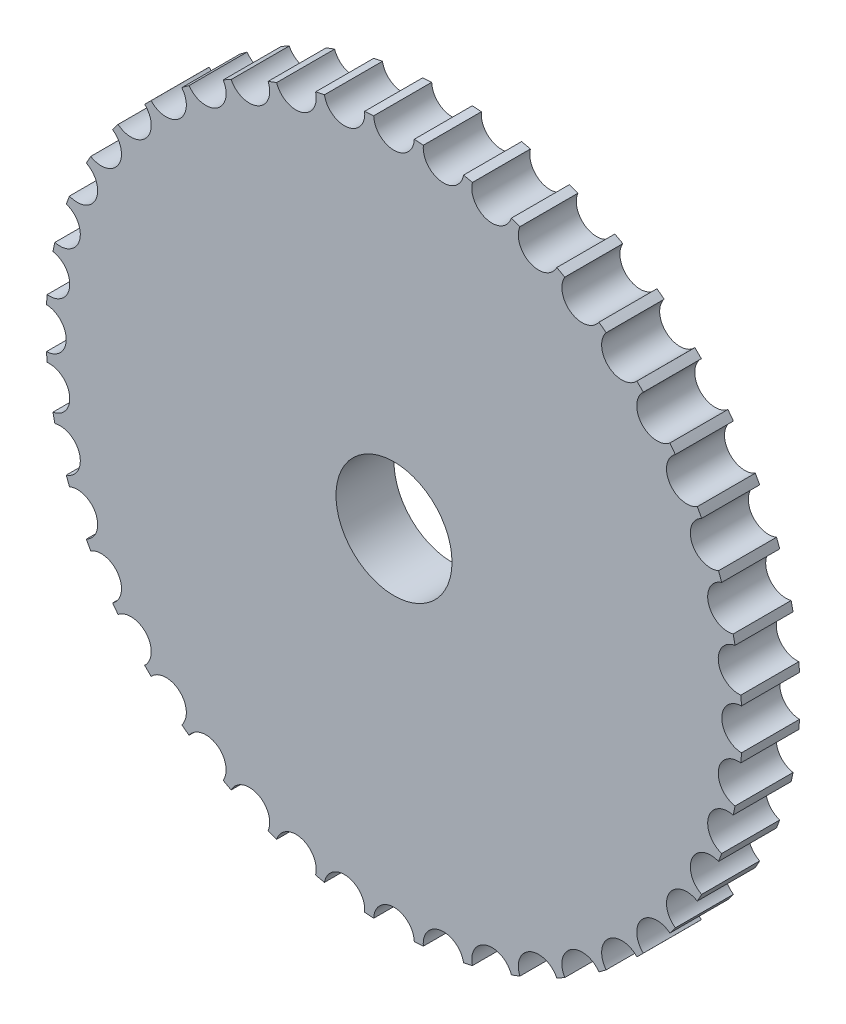
SolidWorks part; units mm, degrees
ref_plane "Front Plane" through (0, 0, 0) normal (0, 0, 1) x (1, 0, 0)
ref_plane "Top Plane" through (0, 0, 0) normal (0, 1, 0) x (1, 0, 0)
ref_plane "Right Plane" through (0, 0, 0) normal (1, 0, 0) x (0, 0, -1)
sketch "Sketch1" plane through (0, 0, 0) normal (0, 0, 1) x (1, 0, 0)
  circle A0 centre (0, 0) radius 76.2
  circle A1 centre (0, 0) radius 12.7
  dimension "D1" = 152.4
  dimension "D2" = 25.4
extrude "Boss-Extrude1" add sketch "Sketch1" along normal blind 12.7
sketch "Sketch2" plane through (0, 0, 12.7) normal (0, 0, 1) x (1, 0, 0)
  line L0 (0, 76.2) -> (0, 0) construction
  circle A0 centre (0, 76.2) radius 4.445
  circle A1 centre (0, 0) radius 76.2 construction
  dimension "D1" = 8.89
extrude "Cut-Extrude1" cut sketch "Sketch2" against normal through all
pattern_circular "CirPattern1" count 44 over 360 about axis through (0, 0, 0) along (0, 0, 1) of "Cut-Extrude1"
